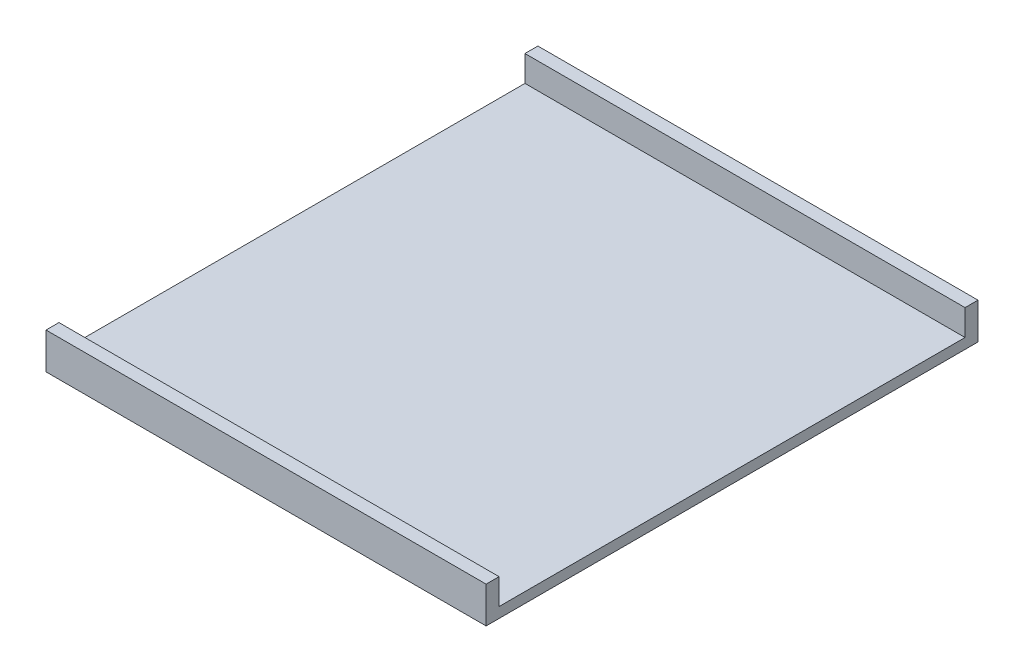
SolidWorks part; units mm, degrees
ref_plane "前视基准面" through (0, 0, 0) normal (0, 0, 1) x (1, 0, 0)
ref_plane "上视基准面" through (0, 0, 0) normal (0, 1, 0) x (1, 0, 0)
ref_plane "右视基准面" through (0, 0, 0) normal (1, 0, 0) x (0, 0, -1)
sketch "草图1" plane through (0, 0, 0) normal (0, 0, 1) x (1, 0, 0)
  line L0 (0, 0) -> (-55, 0) construction
  line L1 (0, 0) -> (55, 0) construction
  line L2 (-55, 0) -> (-55, 3)
  line L3 (-55, 3) -> (-57.5, 3)
  line L4 (-57.5, 3) -> (-57.5, 6)
  line L6 (-62.5, 6) -> (-62.5, 3)
  line L7 (-62.5, 3) -> (-65, 3)
  line L8 (-65, 3) -> (-65, 0)
  line L9 (-65, 0) -> (-55, 0)
  line L10 (0, 0) -> (0, 17.1237) construction
  line L11 (65, 0) -> (55, 0)
  line L12 (65, 3) -> (65, 0)
  line L13 (62.5, 3) -> (65, 3)
  line L14 (62.5, 6) -> (62.5, 3)
  line L15 (57.5, 6) -> (62.5, 6)
  line L16 (57.5, 3) -> (57.5, 6)
  line L17 (55, 3) -> (57.5, 3)
  line L18 (55, 0) -> (55, 3)
  line L19 (-57.5, 6) -> (-62.5, 6)
extrude "凸台-拉伸1" add sketch "草图1" along normal blind 30
sketch "草图2" plane through (0, 6, 0) normal (0, 1, 0) x (1, 0, 0)
  line L4 (0, -110) -> (-85, -110)
  line L5 (0, -110) -> (85, -110)
  line L6 (-85, -110) -> (-85, 80)
  line L7 (-85, 80) -> (85, 80)
  line L8 (85, 80) -> (85, -110)
extrude "凸台-拉伸2" add sketch "草图2" along normal blind 4
sketch "草图3" plane through (0, 10, 0) normal (0, 1, 0) x (1, 0, 0)
  line L0 (-85, 80) -> (-85, 75)
  line L1 (-85, 80) -> (-85, -110) construction
  line L2 (-85, 75) -> (80, 75)
  line L4 (80, -105) -> (-85, -105)
  line L5 (-85, -105) -> (-85, -110)
  line L6 (-85, -110) -> (85, -110) construction
  line L7 (-85, -110) -> (85, -110)
  line L8 (85, -110) -> (85, -105)
  line L9 (85, 80) -> (-85, 80)
  line L10 (80, 75) -> (85, 75)
  line L11 (80, -105) -> (85, -105)
  line L12 (85, 75) -> (85, 80)
extrude "凸台-拉伸3" add sketch "草图3" along normal blind 10
